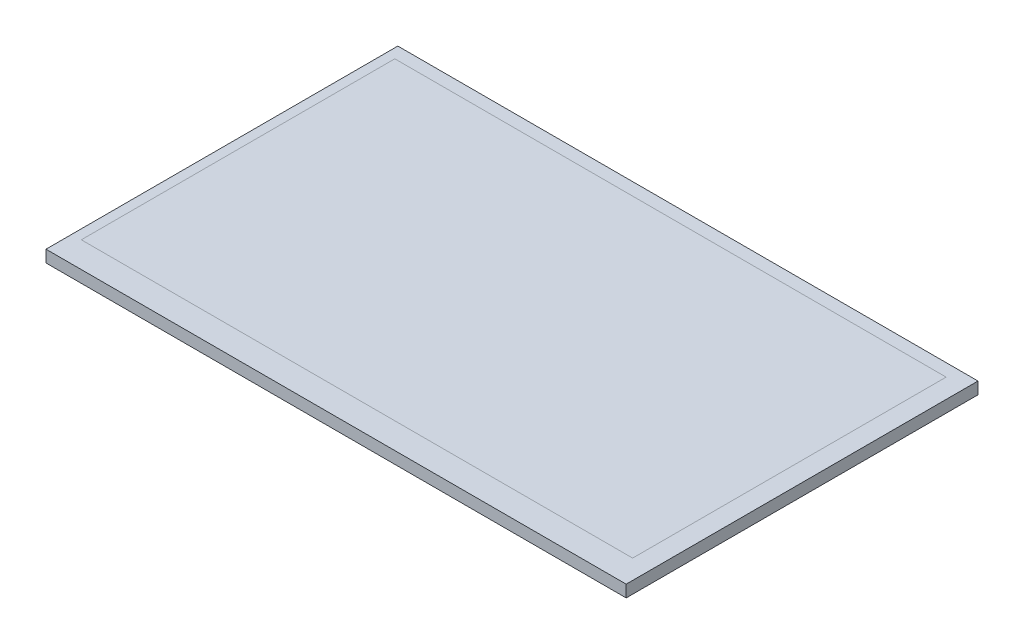
SolidWorks part; units mm, degrees
material "6061-T6 (SS)"
ref_plane "Front Plane" through (0, 0, 0) normal (0, 0, 1) x (1, 0, 0)
ref_plane "Top Plane" through (0, 0, 0) normal (0, 1, 0) x (1, 0, 0)
ref_plane "Right Plane" through (0, 0, 0) normal (1, 0, 0) x (0, 0, -1)
sketch "Sketch1" plane through (0, 0, 0) normal (0, 1, 0) x (1, 0, 0)
  line L1 (-82.45, 50) -> (82.45, 50)
  line L2 (-82.45, 50) -> (-82.45, -50)
  line L3 (-82.45, -50) -> (82.45, -50)
  line L4 (82.45, 50) -> (82.45, -50)
  line L5 (-82.45, 50) -> (82.45, -50) construction
  line L6 (-82.45, -50) -> (82.45, 50) construction
  point P0 (0, 0)
  dimension "D1" = 164.9
  dimension "D2" = 100
extrude "Boss-Extrude1" add sketch "Sketch1" along normal blind 3.4
sketch "Sketch2" plane through (0, 3.4, 0) normal (0, 1, 0) x (1, 0, 0)
  line L0 (82.45, -50) -> (82.45, 50) construction
  line L1 (-79.74, 46.43) -> (76.96, 46.43)
  line L2 (-79.74, 46.43) -> (-79.74, -42.67)
  line L3 (-79.74, -42.67) -> (76.96, -42.67)
  line L4 (76.96, 46.43) -> (76.96, -42.67)
  line L5 (-79.74, 46.43) -> (76.96, -42.67) construction
  line L6 (-79.74, -42.67) -> (76.96, 46.43) construction
  line L7 (82.45, 50) -> (-82.45, 50) construction
  point P0 (-1.39, 1.88)
  point P5 (-2.2108, 9.6087)
  point P6 (-18.5371, 1.1054)
  dimension "D1" = 89.1
  dimension "D2" = 156.7
  dimension "D3" = 5.49
  dimension "D4" = 3.57
split line "Split Line1"
